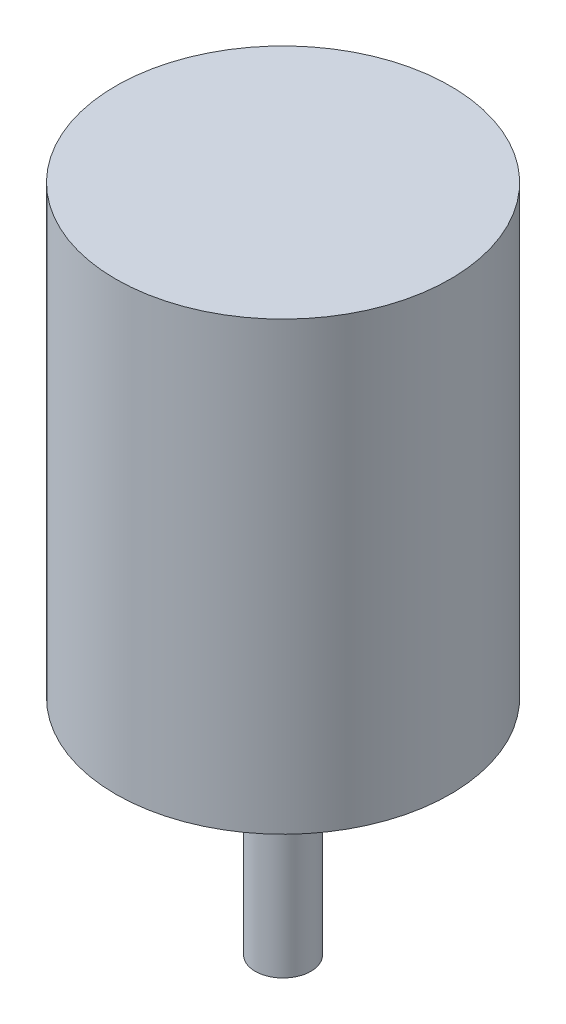
SolidWorks part; units mm, degrees
ref_plane "Front Plane" through (0, 0, 0) normal (0, 0, 1) x (1, 0, 0)
ref_plane "Top Plane" through (0, 0, 0) normal (0, 1, 0) x (1, 0, 0)
ref_plane "Right Plane" through (0, 0, 0) normal (1, 0, 0) x (0, 0, -1)
sketch "Sketch1" plane through (0, 0, 0) normal (0, 1, 0) x (1, 0, 0)
  circle A0 centre (0, 0) radius 2.5
extrude "Boss-Extrude1" add sketch "Sketch1" along normal blind 20
sketch "Sketch2" plane through (0, 20, 0) normal (0, 1, 0) x (1, 0, 0)
  circle A0 centre (0, 0) radius 15
extrude "Boss-Extrude2" add sketch "Sketch2" along normal blind 40
